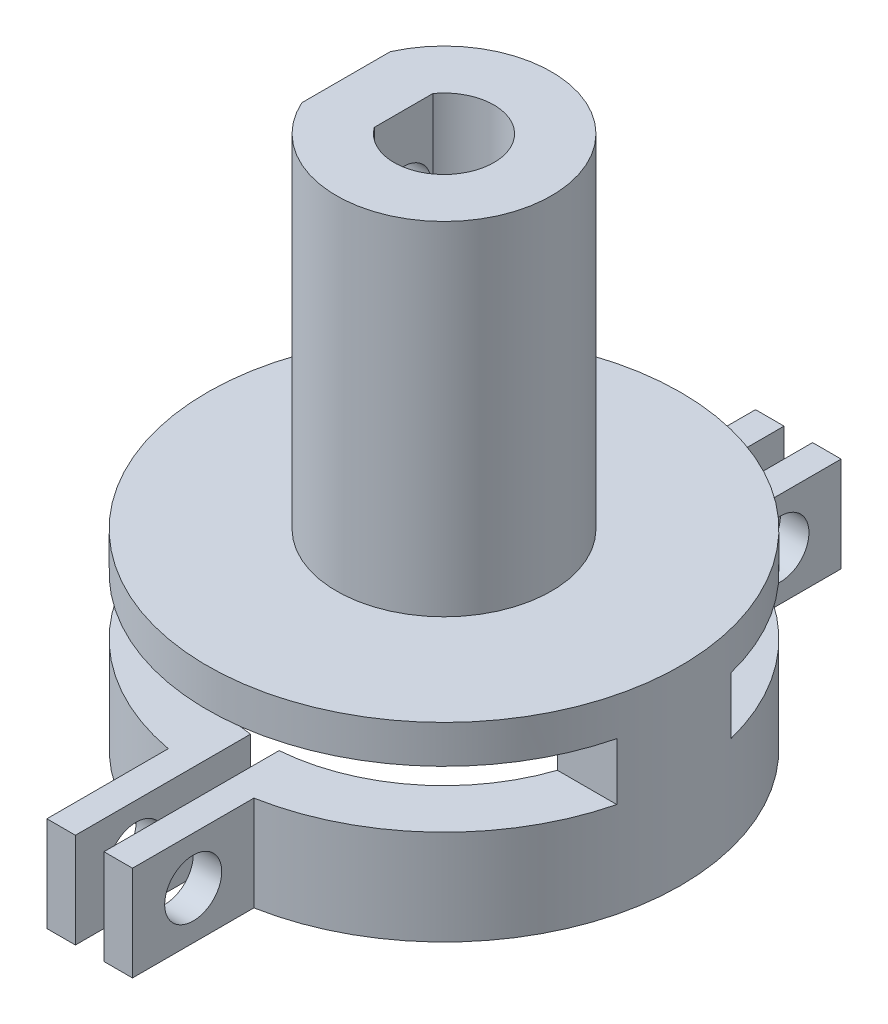
SolidWorks part; units mm, degrees
ref_plane "Front Plane" through (0, 0, 0) normal (0, 0, 1) x (1, 0, 0)
ref_plane "Top Plane" through (0, 0, 0) normal (0, 1, 0) x (1, 0, 0)
ref_plane "Right Plane" through (0, 0, 0) normal (1, 0, 0) x (0, 0, -1)
sketch "Sketch1" plane through (0, 0, 0) normal (0, 1, 0) x (1, 0, 0)
  line L0 (-2.1494, 1.55) -> (-2.1494, -1.55) construction
  line L1 (-5.1494, 2.3251) -> (-5.1494, -2.3251)
  line L2 (-2.1244, 1.5419) -> (-2.1244, -1.5419)
  arc A0 (-2.1494, -1.55) -> (-2.1494, 1.55) centre (0, 0) ccw construction
  arc A1 (-5.1494, -2.3251) -> (-5.1494, 2.3251) centre (0, 0) ccw
  arc A2 (-2.1244, -1.5419) -> (-2.1244, 1.5419) centre (0, 0) ccw
  dimension "D1" = 5.3
  dimension "D2" = 3.1
  dimension "D3" = 3
  dimension "D4" = 0.025
extrude "Boss-Extrude1" add sketch "Sketch1" along normal blind 18
sketch "Sketch2" plane through (0, 0, 0) normal (0, -1, 0) x (1, 0, 0)
  circle A0 centre (0, 0) radius 9.45
  circle A1 centre (0, 0) radius 12.45
  dimension "D1" = 18.9
  dimension "D2" = 3
extrude "Boss-Extrude2" add sketch "Sketch2" along normal blind 10 separate body
sketch "Sketch3" plane through (0, 0, 0) normal (0, -1, 0) x (1, 0, 0)
  circle A0 centre (0, 0) radius 12.45 construction
  circle A1 centre (0, 0) radius 12.45
extrude "Boss-Extrude3" add sketch "Sketch3" along normal blind 2
sketch "Sketch4" plane through (-5.1494, 0, 0) normal (-1, 0, 0) x (0, 0, 1)
  line L0 (0, 18) -> (0, 0) construction
  line L1 (-2.3251, 18) -> (2.3251, 18) construction
  line L2 (0, 9) -> (2.3251, 9) construction
  line L3 (2.3251, 18) -> (2.3251, 0) construction
  circle A0 centre (0, 14) radius 1.45
  circle A1 centre (0, 4) radius 1.45
  dimension "D1" = 2.9
  dimension "D2" = 2.9
  dimension "D3" = 10
extrude "Cut-Extrude1" cut sketch "Sketch4" against normal up to next
sketch "Sketch5" plane through (0, -10, 0) normal (0, -1, 0) x (1, 0, 0)
  line L0 (0, 0) -> (-12.45, 0) construction
  line L1 (0, 9.45) -> (0, 12.45) construction
  line L2 (-8.9612, 3) -> (-12.0831, 3)
  line L3 (-8.9612, -3) -> (-12.0831, -3)
  line L4 (0, 3) -> (-12.45, 3) construction
  line L5 (0, -3) -> (-12.45, -3) construction
  line L6 (8.9612, -3) -> (12.0831, -3)
  line L7 (8.9612, 3) -> (12.0831, 3)
  circle A0 centre (0, 0) radius 9.45 construction
  circle A1 centre (0, 0) radius 12.45
  arc A2 (-12.0831, -3) -> (12.0831, -3) centre (0, 0) ccw
  arc A3 (-8.9612, -3) -> (8.9612, -3) centre (0, 0) ccw
  arc A4 (8.9612, 3) -> (-8.9612, 3) centre (0, 0) ccw
  arc A5 (12.0831, 3) -> (-12.0831, 3) centre (0, 0) ccw
  dimension "D1" = 0
  dimension "D2" = 3
  dimension "D3" = 3
extrude "Cut-Extrude2" cut sketch "Sketch5" along normal blind 3 from surface at -8 starting at face at (0, -2, -9.45)
sketch "Sketch6" plane through (0, -10, 0) normal (0, -1, 0) x (1, 0, 0)
  line L0 (0, 0) -> (0, 12.45) construction
  line L1 (0, 0) -> (12.45, 0) construction
  line L2 (0.75, 9.4202) -> (0.75, 12.4274)
  line L3 (-0.75, 9.4202) -> (-0.75, 12.4274)
  line L4 (-0.75, 0) -> (-0.75, 12.45) construction
  line L5 (0.75, 0) -> (0.75, 12.45) construction
  line L6 (0.75, -9.4202) -> (0.75, -12.4274)
  line L7 (-0.75, -9.4202) -> (-0.75, -12.4274)
  circle A0 centre (0, 0) radius 12.45 construction
  circle A1 centre (0, 0) radius 9.45 construction
  arc A2 (-0.75, -9.4202) -> (0.75, -9.4202) centre (0, 0) ccw
  arc A3 (-0.75, -12.4274) -> (0.75, -12.4274) centre (0, 0) ccw
  arc A4 (0.75, 9.4202) -> (-0.75, 9.4202) centre (0, 0) ccw
  arc A5 (0.75, 12.4274) -> (-0.75, 12.4274) centre (0, 0) ccw
  dimension "D1" = 0.75
  dimension "D2" = 0.75
extrude "Cut-Extrude3" cut sketch "Sketch6" against normal up to next
sketch "Sketch7" plane through (0, -10, 0) normal (0, -1, 0) x (1, 0, 0)
  line L0 (-0.75, 12.4274) -> (-0.75, 18.6274)
  line L1 (-0.75, 18.6274) -> (-2.25, 18.6274)
  line L2 (-2.25, 18.6274) -> (-2.25, 12.245)
  line L3 (0, 0) -> (0, 12.45) construction
  line L4 (0, 0) -> (12.45, 0) construction
  line L5 (2.25, 18.6274) -> (2.25, 12.245)
  line L6 (0.75, 18.6274) -> (2.25, 18.6274)
  line L7 (0.75, 12.4274) -> (0.75, 18.6274)
  line L8 (0.75, -12.4274) -> (0.75, -18.6274)
  line L9 (0.75, -18.6274) -> (2.25, -18.6274)
  line L10 (2.25, -18.6274) -> (2.25, -12.245)
  line L11 (-2.25, -18.6274) -> (-2.25, -12.245)
  line L12 (-0.75, -18.6274) -> (-2.25, -18.6274)
  line L13 (-0.75, -12.4274) -> (-0.75, -18.6274)
  arc A0 (-0.75, 12.4274) -> (-0.75, -12.4274) centre (0, 0) ccw construction
  arc A1 (12.0831, 3) -> (-12.0831, 3) centre (0, 0) ccw construction
  arc A2 (0.75, -12.4274) -> (0.75, 12.4274) centre (0, 0) ccw construction
  arc A7 (0.75, -12.4274) -> (0.75, 12.4274) centre (0, 0) ccw
  arc A8 (-0.75, 12.4274) -> (-0.75, -12.4274) centre (0, 0) ccw
  arc M8 (-0.75, 12.4274) -> (-0.75, -12.4274) centre (0, 0) ccw
  dimension "D1" = 6.2
  dimension "D2" = 1.5
extrude "Boss-Extrude4" add sketch "Sketch7" against normal up to surface (5 mm away) contours L1 L2 L0 M8 | A7 L5 L6 L7 | L13 L11 L12 M8 | A7 L8 L9 L10 up to face at (6.2637, -5, 7.7349)
sketch "Sketch8" plane through (-2.25, 0, 0) normal (-1, 0, 0) x (0, 0, 1)
  line L2 (-18.6274, -5) -> (-18.6274, -10) construction
  line L3 (-12.245, -5) -> (-18.6274, -5) construction
  line L4 (0, 0) -> (0, -10) construction
  line L5 (-12.245, -10) -> (12.245, -10) construction
  circle A0 centre (-15.4362, -7.5) radius 1.5
  circle A2 centre (15.4362, -7.5) radius 1.5
  point P14 (-18.6274, -7.5)
  point P18 (-15.4362, -5)
  dimension "D1" = 3
extrude "Cut-Extrude4" cut sketch "Sketch8" against normal through all
